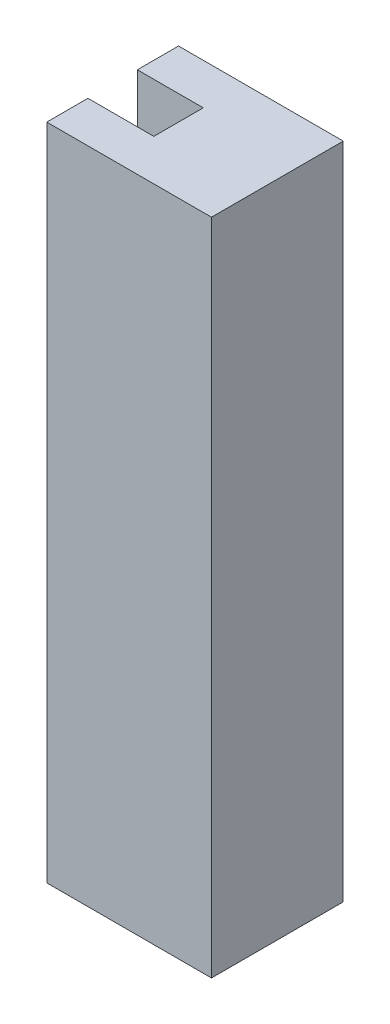
SolidWorks part; units mm, degrees
ref_plane "Спереди" through (0, 0, 0) normal (0, 0, 1) x (1, 0, 0)
ref_plane "Сверху" through (0, 0, 0) normal (0, 1, 0) x (1, 0, 0)
ref_plane "Справа" through (0, 0, 0) normal (1, 0, 0) x (0, 0, -1)
sketch "Эскиз1" plane through (0, 0, 0) normal (0, 1, 0) x (1, 0, 0)
  line L1 (0, 0) -> (20, 0)
  line L2 (0, 0) -> (0, -16)
  line L3 (0, -16) -> (20, -16)
  line L4 (20, 0) -> (20, -16)
extrude "Вытянуть1" add sketch "Эскиз1" along normal blind 80
sketch "Эскиз2" plane through (0, 80, 0) normal (0, 1, 0) x (1, 0, 0)
  line L0 (0, -8) -> (28.2227, -8) construction
  line L1 (0, 0) -> (0, -16) construction
  line L3 (-5.093, -5) -> (8, -5)
  line L4 (-5.093, -5) -> (-5.093, -11)
  line L5 (-5.093, -11) -> (8, -11)
  line L6 (8, -5) -> (8, -11)
  dimension "D1" = 8
extrude "Вытянуть2" cut sketch "Эскиз2" against normal through all
